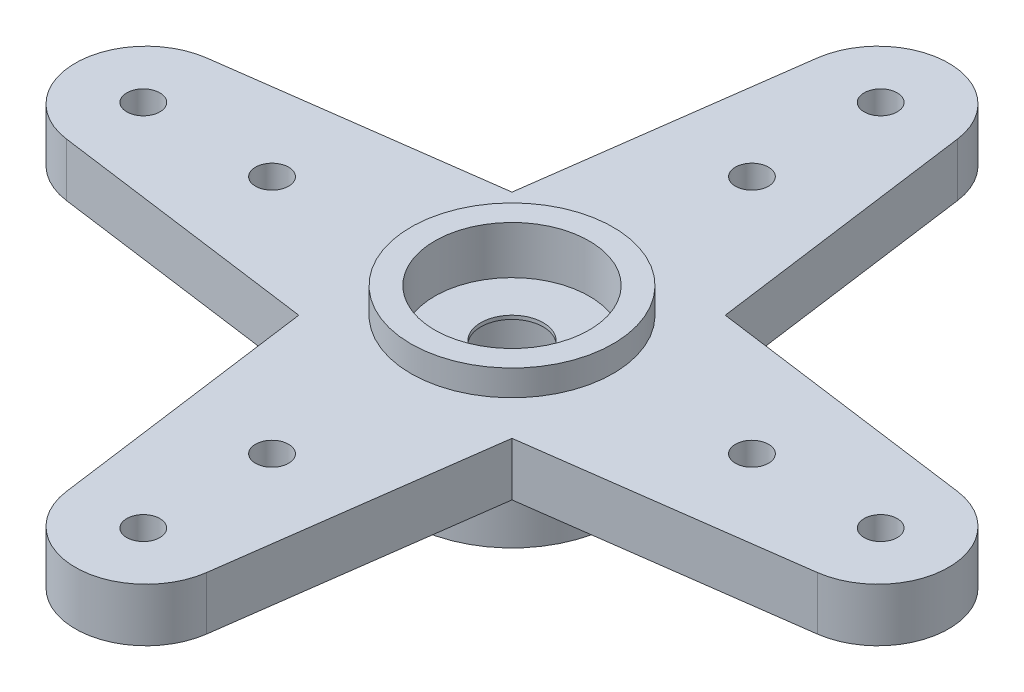
SolidWorks part; units mm, degrees
ref_plane "Front Plane" through (0, 0, 0) normal (0, 0, 1) x (1, 0, 0)
ref_plane "Top Plane" through (0, 0, 0) normal (0, 1, 0) x (1, 0, 0)
ref_plane "Right Plane" through (0, 0, 0) normal (1, 0, 0) x (0, 0, -1)
sketch "Sketch1" plane through (0, 0, 0) normal (0, 1, 0) x (1, 0, 0)
  circle A0 centre (0, 0) radius 1.925
  circle A1 centre (0, 0) radius 2.875
  dimension "D1" = 3.85
  dimension "D2" = 5.75
extrude "Boss-Extrude1" add sketch "Sketch1" along normal blind 2
sketch "Sketch2" plane through (0, 2, 0) normal (0, 1, 0) x (1, 0, 0)
  line L0 (0, 0) -> (0, 11.875) construction
  line L1 (0, 0) -> (0, -11.875) construction
  line L2 (-11.875, 0) -> (0, 0) construction
  line L3 (0, 0) -> (11.875, 0) construction
  line L4 (-1.9075, 10.2088) -> (-2.8991, 2.8991)
  line L5 (-10.2088, 1.9075) -> (-2.8991, 2.8991)
  line L6 (1.9075, 10.2088) -> (2.8991, 2.8991)
  line L7 (-10.2088, -1.9075) -> (-2.8991, -2.8991)
  line L8 (1.9075, -10.2088) -> (2.8991, -2.8991)
  line L9 (-1.9075, -10.2088) -> (-2.8991, -2.8991)
  line L10 (10.2088, 1.9075) -> (2.8991, 2.8991)
  line L11 (10.2088, -1.9075) -> (2.8991, -2.8991)
  circle A0 centre (0, 0) radius 4.1 construction
  circle A1 centre (0, 9.95) radius 1.925
  circle A2 centre (9.95, 0) radius 1.925
  circle A3 centre (0, -9.95) radius 1.925
  circle A4 centre (-9.95, 0) radius 1.925
  circle M9 centre (0, 0) radius 2.875
  circle M10 centre (0, 0) radius 1.925
  dimension "D2" = 8.2
  dimension "D3" = 3.85
  dimension "D1" = 23.75
  dimension "D4" = 5.7983
extrude "Boss-Extrude2" add sketch "Sketch2" along normal blind 1.45 contours A4 | A4 L7 L9 A3 L8 L11 A2 L10 L6 A1 L4 L5 M9 | M9 M10 | M10 | A3 | A2 | A1
sketch "Sketch3" plane through (0, 3.45, 0) normal (0, 1, 0) x (1, 0, 0)
  circle A1 centre (0, 0) radius 2.75
  circle A2 centre (0, 0) radius 2.1
  dimension "D1" = 5.5
  dimension "D2" = 0.65
extrude "Boss-Extrude3" add sketch "Sketch3" along normal blind 0.7
sketch "Sketch5" plane through (0, 4.15, 0) normal (0, 1, 0) x (1, 0, 0)
  circle A0 centre (0, 0) radius 2.1 construction
  circle A1 centre (0, 0) radius 2.1
extrude "Cut-Extrude1" cut sketch "Sketch5" against normal blind 1.3
sketch "Sketch6" plane through (0, 2.85, 0) normal (0, 1, 0) x (1, 0, 0)
  circle A0 centre (0, 0) radius 0.85
  dimension "D1" = 1.7
extrude "Cut-Extrude2" cut sketch "Sketch6" against normal through all
sketch "Sketch7" plane through (0, 3.45, 0) normal (0, 1, 0) x (1, 0, 0)
  line L0 (0, 11.875) -> (0, 0) construction
  line L1 (0, 0) -> (0, -11.875) construction
  line L2 (11.875, 0) -> (0, 0) construction
  line L3 (0, 0) -> (-11.875, 0) construction
  line L5 (0, 6.525) -> (6.525, 0) construction
  line L6 (6.525, 0) -> (0, -6.525) construction
  line L7 (0, -6.525) -> (-6.525, 0) construction
  line L8 (-6.525, 0) -> (0, 6.525) construction
  line L9 (0, 10.025) -> (10.025, 0) construction
  line L10 (10.025, 0) -> (0, -10.025) construction
  line L11 (0, -10.025) -> (-10.025, 0) construction
  line L12 (-10.025, 0) -> (0, 10.025) construction
  arc A0 (1.9075, 10.2088) -> (-1.9075, 10.2088) centre (0, 9.95) ccw construction
  arc A1 (-1.9075, -10.2088) -> (1.9075, -10.2088) centre (0, -9.95) ccw construction
  arc A2 (10.2088, -1.9075) -> (10.2088, 1.9075) centre (9.95, 0) ccw construction
  arc A3 (-10.2088, 1.9075) -> (-10.2088, -1.9075) centre (-9.95, 0) ccw construction
  circle A4 centre (0, 10.025) radius 0.45
  circle A5 centre (0, 6.525) radius 0.45
  circle A6 centre (6.525, 0) radius 0.45
  circle A7 centre (10.025, 0) radius 0.45
  circle A8 centre (0, -6.525) radius 0.45
  circle A9 centre (0, -10.025) radius 0.45
  circle A10 centre (-6.525, 0) radius 0.45
  circle A11 centre (-10.025, 0) radius 0.45
  dimension "D1" = 0.9
  dimension "D2" = 12.15
  dimension "D3" = 19.15
extrude "Cut-Extrude3" cut sketch "Sketch7" against normal through all
sketch "Sketch8" plane through (0, 2, 0) normal (0, -1, 0) x (1, 0, 0)
  circle A0 centre (0, 0) radius 1.925 construction
  circle A1 centre (0, 0) radius 1.925
extrude "Cut-Extrude4" cut sketch "Sketch8" against normal blind 0.75
